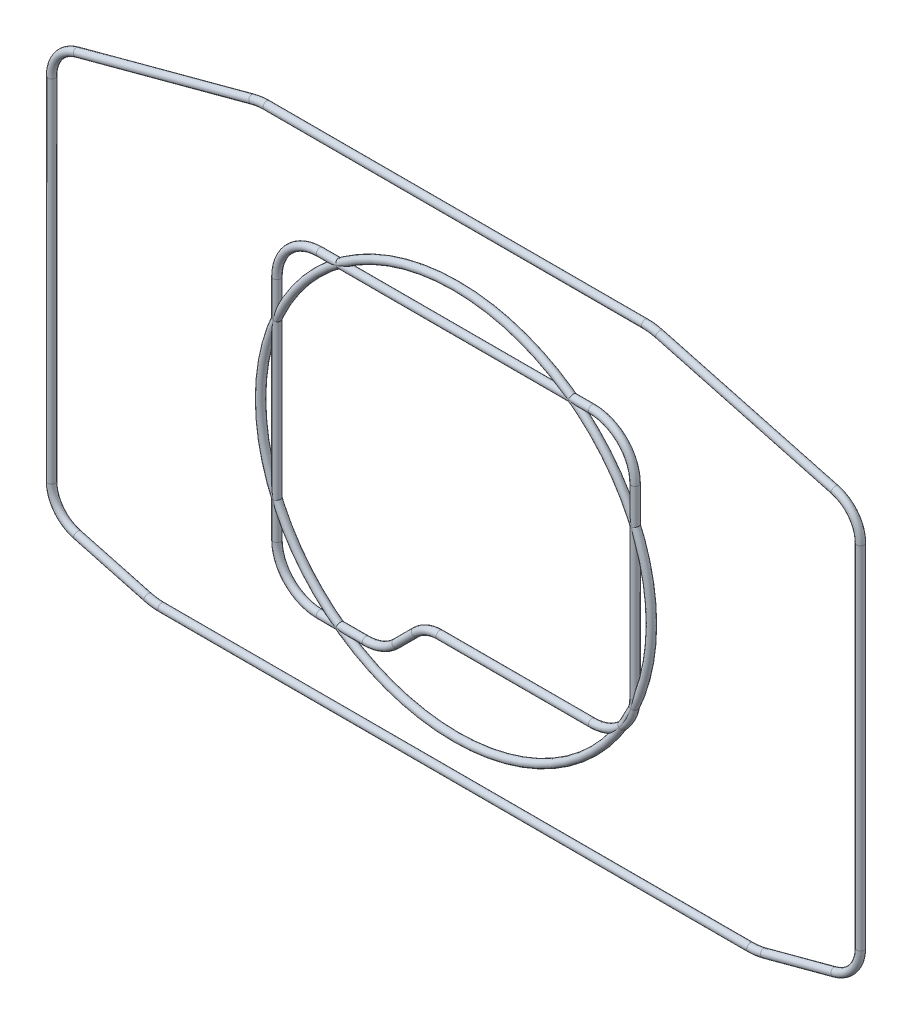
SolidWorks part; units mm, degrees
material "O-Ring (NBR)"
ref_plane "Front Plane" through (0, 0, 0) normal (0, 0, 1) x (1, 0, 0)
ref_plane "Top Plane" through (0, 0, 0) normal (0, 1, 0) x (1, 0, 0)
ref_plane "Right Plane" through (0, 0, 0) normal (1, 0, 0) x (0, 0, -1)
sketch "Sketch1" plane through (0, 0, 0) normal (0, 0, 1) x (1, 0, 0)
  line L0 (55, -46.4) -> (-6.5797, -46.4)
  line L1 (-24.1167, -58.3037) -> (-16.1963, -50.3833)
  line L2 (55, -44.5) -> (-6.5797, -44.5) construction
  line L3 (-55, -63.4) -> (-36.4203, -63.4)
  line L4 (-72.4, 46) -> (-72.4, -46)
  line L5 (-25.4602, -56.9602) -> (-17.5398, -49.0398) construction
  line L6 (-55, -61.5) -> (-36.4203, -61.5) construction
  line L7 (-70.5, 46) -> (-70.5, -46) construction
  line L8 (55, 61.5) -> (-55, 61.5) construction
  line L9 (55, 63.4) -> (-55, 63.4)
  line L10 (72.4, -29) -> (72.4, 46)
  line L11 (70.5, -29) -> (70.5, 46) construction
  arc A0 (-70.5, -46) -> (-55, -61.5) centre (-55, -46) ccw construction
  arc A1 (70.5, -29) -> (55, -44.5) centre (55, -29) cw construction
  arc A2 (-17.5398, -49.0398) -> (-6.5797, -44.5) centre (-6.5797, -60) cw construction
  arc A3 (70.5, 46) -> (55, 61.5) centre (55, 46) ccw construction
  arc A4 (-55, 61.5) -> (-70.5, 46) centre (-55, 46) ccw construction
  arc A5 (-25.4602, -56.9602) -> (-36.4203, -61.5) centre (-36.4203, -46) cw construction
  arc A6 (-16.1963, -50.3833) -> (-6.5797, -46.4) centre (-6.5797, -60) cw
  arc A7 (-24.1167, -58.3037) -> (-36.4203, -63.4) centre (-36.4203, -46) cw
  arc A8 (-72.4, -46) -> (-55, -63.4) centre (-55, -46) ccw
  arc A9 (-55, 63.4) -> (-72.4, 46) centre (-55, 46) ccw
  arc A10 (72.4, 46) -> (55, 63.4) centre (55, 46) ccw
  arc A11 (72.4, -29) -> (55, -46.4) centre (55, -29) cw
  dimension "D1" = 1.9
sketch "Sketch2" plane through (0, 0, 0) normal (0, 1, 0) x (1, 0, 0)
  circle A0 centre (72.4, 0) radius 1.5
  dimension "D1" = 3
sweep "Sweep1" add profiles "Sketch2" path "Sketch1"
sketch "Sketch3" plane through (0, 0, 0) normal (0, 0, 1) x (1, 0, 0)
  line L0 (-163.5, 70.7219) -> (-163.5, -71.1098)
  line L1 (-124.694, -92.2504) -> (-153.1235, -84.6327)
  line L2 (-119, -93) -> (119, -93)
  line L3 (124.694, -92.2504) -> (153.1235, -84.6327)
  line L4 (163.5, -71.1098) -> (163.5, 70.7219)
  line L5 (153.1235, 84.2449) -> (82.194, 103.2504)
  line L6 (76.5, 104) -> (-76.5, 104)
  line L7 (-82.194, 103.2504) -> (-153.1235, 84.2449)
  line L8 (-161.5, 70.7219) -> (-161.5, -71.1098) construction
  line L9 (-124.1764, -90.3185) -> (-152.6058, -82.7009) construction
  line L10 (-119, -91) -> (119, -91) construction
  line L11 (124.1764, -90.3185) -> (152.6058, -82.7009) construction
  line L12 (161.5, -71.1098) -> (161.5, 70.7219) construction
  line L13 (152.6058, 82.313) -> (81.6764, 101.3185) construction
  line L14 (76.5, 102) -> (-76.5, 102) construction
  line L15 (-81.6764, 101.3185) -> (-152.6058, 82.313) construction
  line L16 (0, 0) -> (0, 80.8457) construction
  line L17 (0, 0) -> (192.9468, 0) construction
  arc A0 (-161.5, 70.7219) -> (-152.6058, 82.313) centre (-149.5, 70.7219) cw construction
  arc A1 (161.5, 70.7219) -> (152.6058, 82.313) centre (149.5, 70.7219) ccw construction
  arc A2 (-153.1235, -84.6327) -> (-163.5, -71.1098) centre (-149.5, -71.1098) cw
  arc A3 (-124.694, -92.2504) -> (-119, -93) centre (-119, -71) ccw
  arc A4 (124.694, -92.2504) -> (119, -93) centre (119, -71) cw
  arc A5 (153.1235, -84.6327) -> (163.5, -71.1098) centre (149.5, -71.1098) ccw
  arc A6 (163.5, 70.7219) -> (153.1235, 84.2449) centre (149.5, 70.7219) ccw
  arc A7 (76.5, 104) -> (82.194, 103.2504) centre (76.5, 82) cw
  arc A8 (-82.194, 103.2504) -> (-76.5, 104) centre (-76.5, 82) cw
  arc A9 (-163.5, 70.7219) -> (-153.1235, 84.2449) centre (-149.5, 70.7219) cw
  arc A10 (-152.6058, -82.7009) -> (-161.5, -71.1098) centre (-149.5, -71.1098) cw construction
  arc A11 (-124.1764, -90.3185) -> (-119, -91) centre (-119, -71) ccw construction
  arc A12 (124.1764, -90.3185) -> (119, -91) centre (119, -71) cw construction
  arc A13 (152.6058, -82.7009) -> (161.5, -71.1098) centre (149.5, -71.1098) ccw construction
  arc A14 (76.5, 102) -> (81.6764, 101.3185) centre (76.5, 82) cw construction
  arc A15 (-81.6764, 101.3185) -> (-76.5, 102) centre (-76.5, 82) cw construction
  dimension "D3" = 12
  dimension "D5" = 20
  dimension "D6" = 20
  dimension "D7" = 12
  dimension "D1" = 102
  dimension "D2" = 193
  dimension "D4" = 15
  dimension "D8" = 238
  dimension "D9" = 15
  dimension "D10" = 153
  dimension "D11" = 323
  dimension "D12" = 2
sketch "Sketch4" plane through (0, 0, 0) normal (0, 1, 0) x (1, 0, 0)
  circle A0 centre (163.5, 0) radius 1.5
  dimension "D1" = 3
sweep "Sweep2" add profiles "Sketch4" path "Sketch3"
sketch "Sketch6" plane through (0, 0, 0) normal (1, 0, 0) x (0, 0, -1)
  line L0 (0, 0) -> (46.3892, 0) construction
  circle A0 centre (0, 79) radius 1.5
  dimension "D1" = 3
  dimension "D2" = 155
revolve "Revolve1" add sketch "Sketch6" angle 360 about L0
